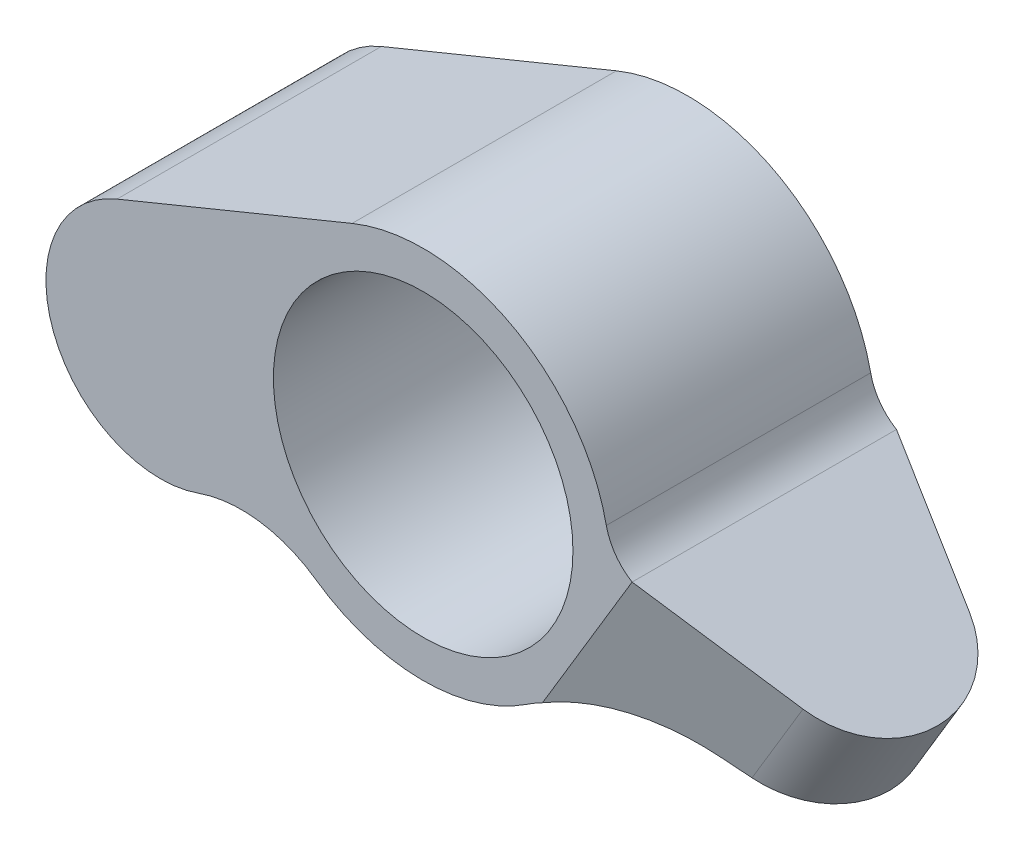
SolidWorks part; units mm, degrees
ref_plane "Alzado" through (0, 0, 0) normal (0, 0, 1) x (1, 0, 0)
ref_plane "Planta" through (0, 0, 0) normal (0, 1, 0) x (1, 0, 0)
ref_plane "Vista lateral" through (0, 0, 0) normal (1, 0, 0) x (0, 0, -1)
sketch "Croquis1" plane through (0, 0, 0) normal (0, 0, 1) x (1, 0, 0)
  line L0 (-34.7514, 8.7088) -> (-8.0675, 19.659)
  line L1 (37.9808, -20.6082) -> (43.3802, -11.5044)
  line L2 (43.3802, -11.5044) -> (23.715, 0.2979)
  line L3 (37.9808, -20.6082) -> (29.127, -16.4148)
  circle A0 centre (0, 0) radius 17
  arc A1 (20.7893, 4.4009) -> (-8.0675, 19.659) centre (0, 0) ccw
  arc A3 (-12.1835, -17.4105) -> (-25.5063, -15.5828) centre (-20.6252, -29.4739) ccw
  arc A4 (29.127, -16.4148) -> (11.7883, -17.6805) centre (21.5753, -32.3593) ccw
  arc A5 (-34.7514, 8.7088) -> (-25.5063, -15.5828) centre (-29.816, -3.3179) ccw
  arc A6 (-12.1835, -17.4105) -> (11.7883, -17.6805) centre (0, 0) ccw
  arc A7 (20.7893, 4.4009) -> (23.715, 0.2979) centre (26.9616, 5.7075) ccw
  point P10 (31.533, 6.9968)
  point P15 (43.0556, -11.3421)
  point P20 (27.1511, 4.7247)
  point P21 (43.3802, -11.5044)
  point P22 (21.5753, 1.8244)
  dimension "D1" = 34
extrude "Saliente-Extruir1" add sketch "Croquis1" along normal blind 30
ref_plane "Plano1" through (6.4114, 10.6828, 0) normal (0.5146, 0.8574, 0) x (0.8574, -0.5146, 0)
sketch "Croquis7" plane through (6.4114, 10.6828, 0) normal (0.5146, 0.8574, 0) x (0.8574, -0.5146, 0)
  line L0 (20.1807, 0) -> (20.1807, 9.2385)
  line L1 (20.1807, 9.2385) -> (56.5826, 4.6192)
  line L6 (36.3589, -5.5467) -> (20.1807, 0)
  line L7 (36.3524, -24.4679) -> (20.1807, -30)
  line L11 (56.5826, 4.6192) -> (52.4967, -37.8744)
  line L12 (52.4967, -37.8744) -> (21.8942, -35.4562)
  line L13 (21.8942, -35.4562) -> (20.1807, -30)
  arc A0 (36.3524, -24.4679) -> (36.3589, -5.5467) centre (33.1157, -15.0062) ccw
  dimension "D1" = 20
extrude "Cortar-Extruir5" cut sketch "Croquis7" against normal through all
